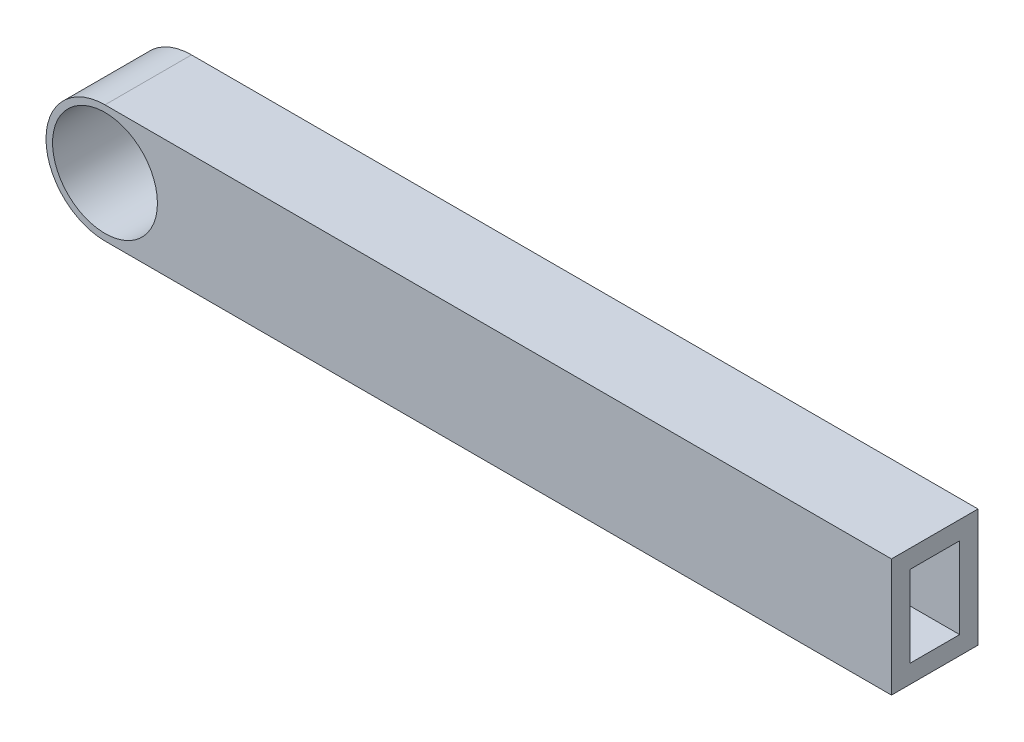
SolidWorks part; units mm, degrees
ref_plane "Front Plane" through (0, 0, 0) normal (0, 0, 1) x (1, 0, 0)
ref_plane "Top Plane" through (0, 0, 0) normal (0, 1, 0) x (1, 0, 0)
ref_plane "Right Plane" through (0, 0, 0) normal (1, 0, 0) x (0, 0, -1)
sketch "Sketch1" plane through (0, 0, 0) normal (0, 0, 1) x (1, 0, 0)
  line L0 (-165, -22.5) -> (-165, 22.5)
  line L1 (-165, -22.5) -> (165, -22.5)
  line L2 (-165, 22.5) -> (165, 22.5)
  line L3 (165, -22.5) -> (165, 22.5)
  line L4 (-165, -22.5) -> (165, 22.5) construction
  line L5 (-165, 22.5) -> (165, -22.5) construction
  point P1 (0, 0)
  dimension "D1" = 45
  dimension "D2" = 330
extrude "Boss-Extrude1" add sketch "Sketch1" along normal blind 33
sketch "Sketch2" plane through (0, 0, 33) normal (0, 0, 1) x (1, 0, 0)
  line L0 (165, -22.5) -> (165, 22.5) construction
  line L1 (-135, 22.5) -> (-173.5211, 35.0696)
  line L2 (-173.5211, 35.0696) -> (-171.5697, -40.1364)
  line L3 (-171.5697, -40.1364) -> (-135, -22.5)
  circle A0 centre (-135, 0) radius 20
  arc A1 (-135, 22.5) -> (-135, -22.5) centre (-135, 0) ccw
  dimension "D1" = 40
  dimension "D2" = 300
extrude "Cut-Extrude1" cut sketch "Sketch2" against normal blind 40
sketch "Sketch3" plane through (165, 0, 0) normal (1, 0, 0) x (0, 0, -1)
  line L0 (-33, -22.5) -> (-33, 22.5) construction
  line L1 (-26, -15.5) -> (-7, -15.5)
  line L2 (-26, -15.5) -> (-26, 15.5)
  line L3 (-26, 15.5) -> (-7, 15.5)
  line L4 (-7, -15.5) -> (-7, 15.5)
  line L5 (-26, -15.5) -> (-7, 15.5) construction
  line L6 (-26, 15.5) -> (-7, -15.5) construction
  line L7 (-33, 22.5) -> (0, 22.5) construction
  line L8 (0, -22.5) -> (0, 22.5) construction
  line L10 (-33, -22.5) -> (0, -22.5) construction
  point P0 (-16.5, 0)
  point P5 (-26, 0)
  dimension "D1" = 7
  dimension "D2" = 7
  dimension "D3" = 7
  dimension "D4" = 7
extrude "Cut-Extrude2" cut sketch "Sketch3" against normal blind 260
